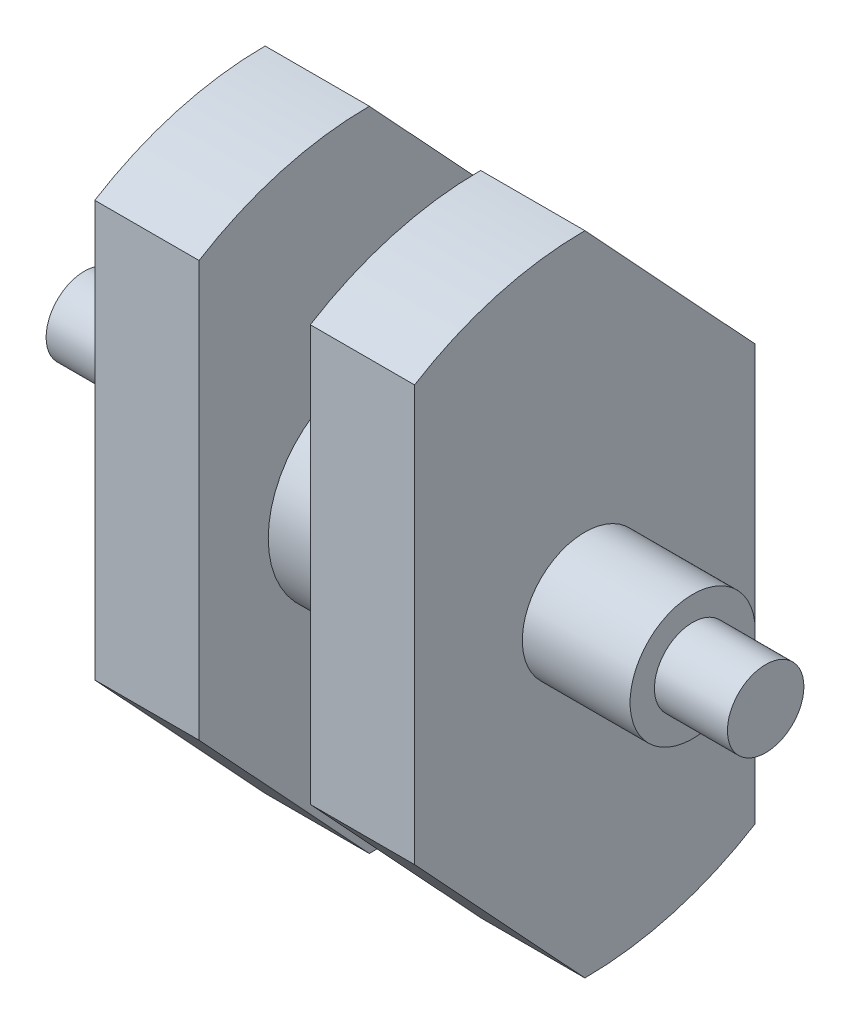
SolidWorks part; units mm, degrees
material "AISI 4340 Aço, normalizado"
ref_plane "Plano frontal" through (0, 0, 0) normal (0, 0, 1) x (1, 0, 0)
ref_plane "Plano superior" through (0, 0, 0) normal (0, 1, 0) x (1, 0, 0)
ref_plane "Plano direito" through (0, 0, 0) normal (1, 0, 0) x (0, 0, -1)
sketch "Esboço1" plane through (0, 0, 0) normal (1, 0, 0) x (0, 0, -1)
  circle A0 centre (0, 0) radius 46.55
  dimension "D1" = 93.1
extrude "Ressalto-extrusão1" add sketch "Esboço1" along normal mid plane 98
sketch "Esboço2" plane through (0, 0, 0) normal (1, 0, 0) x (0, 0, -1)
  line L0 (0, -1000) -> (0, 49000) construction
  line L1 (-1000, 0) -> (49000, 0) construction
  line L2 (24.5, 60.3021) -> (24.5, -60.3021)
  line L3 (-24.5, 60.3021) -> (-24.5, -60.3021)
  line L4 (0, 46.55) -> (24.5, 20.1729)
  line L6 (0, -46.55) -> (-24.5, -20.1729)
  circle A0 centre (0, 0) radius 46.55 construction
  circle A2 centre (0, 0) radius 46.55
  point P8 (24.5, 0)
  dimension "D1" = 24.5
extrude "Corte-extrusão2" cut sketch "Esboço2" against normal through all both and the other way through all contours L3 A2 | L3 A2 L6 | L2 A2 | L2 A2 L4
sketch "Esboço3" plane through (0, 0, 0) normal (1, 0, 0) x (0, 0, -1)
  circle A0 centre (0, 0) radius 9
extrude "Corte-extrusão10" cut sketch "Esboço3" along normal blind 26 from surface at -49 flip side to cut starting at face at (-49, 0, 0)
sketch "Esboço6" plane through (0, 0, 0) normal (1, 0, 0) x (0, 0, -1)
  circle A0 centre (0, 0) radius 9
extrude "Corte-extrusão11" cut sketch "Esboço6" against normal blind 26 from surface at 49 flip side to cut starting at face at (49, 0, 0)
sketch "Esboço7" plane through (49, 0, 0) normal (1, 0, 0) x (0, 0, -1)
  circle A1 centre (0, 0) radius 5.5
extrude "Corte-extrusão12" cut sketch "Esboço7" against normal blind 10.5 from surface at 0 flip side to cut starting at face at (49, 0, -9)
sketch "Esboço8" plane through (-49, 0, 0) normal (-1, 0, 0) x (0, 0, 1)
  circle A0 centre (0, 0) radius 5.5
extrude "Corte-extrusão13" cut sketch "Esboço8" against normal blind 10.5 flip side to cut
sketch "Esboço9" plane through (0, 0, 0) normal (0, 0, 1) x (1, 0, 0)
  line L0 (-8, 39.581) -> (-8, 30.0139) construction
  line L1 (-23, 39.581) -> (23, 39.581) construction
  line L2 (-23, 39.581) -> (-23, -20.1729) construction
  line L3 (0, -1000) -> (0, 49000) construction
  line L4 (8, 39.581) -> (8, 30.0139) construction
  line L5 (-1000, 0) -> (49000, 0) construction
  line L6 (-8, 14.55) -> (8, 14.55) construction
  line L7 (-23, 46.55) -> (23, 46.55) construction
  line L8 (-8, 14.55) -> (-8, 51.4116)
  line L9 (-8, 51.4116) -> (8, 51.4116)
  line L10 (8, 51.4116) -> (8, 14.55)
  line L11 (8, 14.55) -> (-8, 14.55)
  point P16 (0, 14.55)
  dimension "D1" = 15
  dimension "D2" = 32
revolve "Corte-Revolução1" cut sketch "Esboço9" angle 360 about L5
